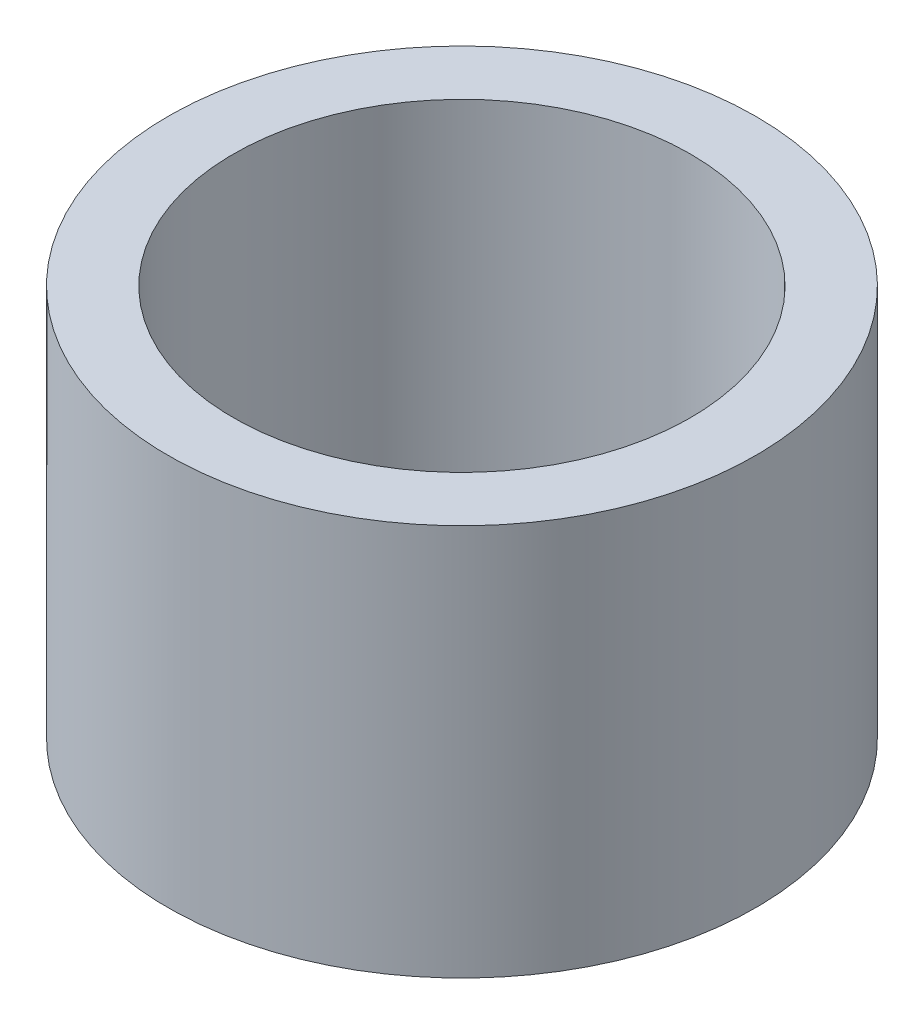
SolidWorks part; units mm, degrees
material "AISI 1020"
ref_plane "Front Plane" through (0, 0, 0) normal (0, 0, 1) x (1, 0, 0)
ref_plane "Top Plane" through (0, 0, 0) normal (0, 1, 0) x (1, 0, 0)
ref_plane "Right Plane" through (0, 0, 0) normal (1, 0, 0) x (0, 0, -1)
sketch "Sketch1" plane through (0, 0, 0) normal (0, 1, 0) x (1, 0, 0)
  circle A0 centre (0, 0) radius 28.575
  circle A1 centre (0, 0) radius 22.225
  dimension "D1" = 57.15
  dimension "D2" = 44.45
extrude "Boss-Extrude1" add sketch "Sketch1" along normal blind 38.1
